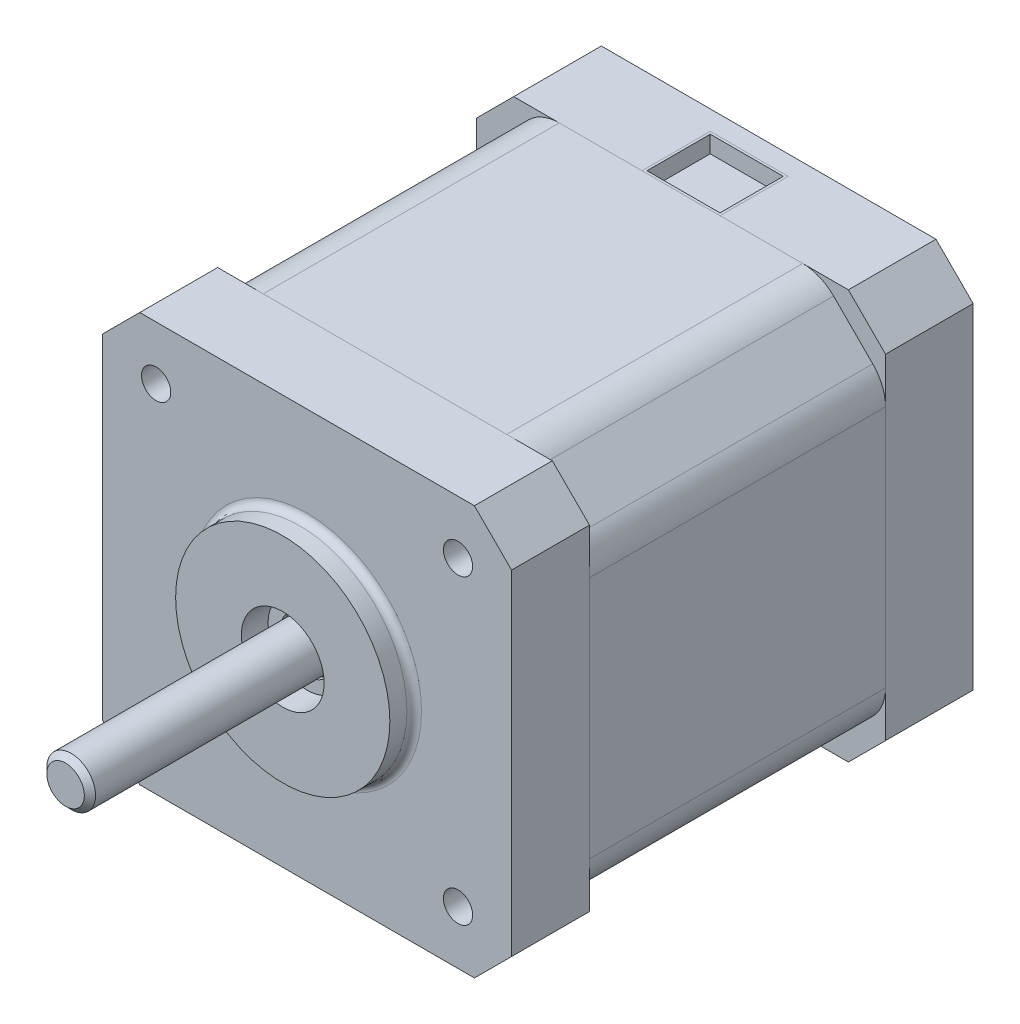
SolidWorks part; units mm, degrees
other "ŞAFT"
other "ARKA"
other "ORTA"
other "ÖN"
other "KABLO"
ref_plane "Front Plane" through (0, 0, 0) normal (0, 0, 1) x (1, 0, 0)
ref_plane "Top Plane" through (0, 0, 0) normal (0, 1, 0) x (1, 0, 0)
ref_plane "Right Plane" through (0, 0, 0) normal (1, 0, 0) x (0, 0, -1)
sketch "Sketch1" plane through (0, 0, 0) normal (0, 0, 1) x (1, 0, 0)
  line L0 (-15.5, 15.5) -> (15.5, 15.5) construction
  line L1 (17.1838, 21) -> (-17.1838, 21)
  line L2 (21, 17.1838) -> (21, -17.1838)
  line L3 (17.1838, -21) -> (-17.1838, -21)
  line L4 (-21, 17.1838) -> (-21, -17.1838)
  line L5 (19.0919, 19.0919) -> (-19.0919, -19.0919) construction
  line L6 (19.0919, -19.0919) -> (-19.0919, 19.0919) construction
  line L7 (15.5, 15.5) -> (15.5, -15.5) construction
  line L8 (15.5, -15.5) -> (-15.5, -15.5) construction
  line L9 (-15.5, -15.5) -> (-15.5, 15.5) construction
  line L10 (17.1838, 21) -> (21, 17.1838)
  line L11 (21, 17.1838) -> (21, 21) construction
  line L12 (21, 21) -> (17.1838, 21) construction
  line L13 (19.0919, 19.0919) -> (21, 21) construction
  line L14 (19.0919, 19.0919) -> (-19.0919, 19.0919) construction
  line L15 (-19.0919, 19.0919) -> (-19.0919, -19.0919) construction
  line L16 (-19.0919, -19.0919) -> (19.0919, -19.0919) construction
  line L17 (19.0919, -19.0919) -> (19.0919, 19.0919) construction
  line L18 (21, -17.1838) -> (17.1838, -21)
  line L19 (-17.1838, -21) -> (-21, -17.1838)
  line L20 (-21, 17.1838) -> (-17.1838, 21)
  line L21 (-19.0919, -19.0919) -> (-21, -21) construction
  line L22 (19.0919, -19.0919) -> (21, -21) construction
  line L23 (-19.0919, 19.0919) -> (-21, 21) construction
  line L24 (21, -17.1838) -> (21, -21) construction
  line L25 (21, -21) -> (17.1838, -21) construction
  line L26 (-17.1838, -21) -> (-21, -21) construction
  line L27 (-21, -21) -> (-21, -17.1838) construction
  line L28 (-21, 17.1838) -> (-21, 21) construction
  line L29 (-21, 21) -> (-17.1838, 21) construction
  circle A0 centre (-15.5, 15.5) radius 1.5 construction
  circle A1 centre (15.5, 15.5) radius 1.5 construction
  circle A2 centre (-15.5, -15.5) radius 1.5 construction
  circle A3 centre (15.5, -15.5) radius 1.5 construction
  point P0 (0, 0)
  dimension "D2" = 3
  dimension "D1" = 42
  dimension "D3" = 31
  dimension "D4" = 54
extrude "Boss-Extrude1" add sketch "Sketch1" against normal blind 8
sketch "Sketch3" plane through (0, 0, -8) normal (0, 0, -1) x (-1, 0, 0)
  line L0 (-19.6881, 15.6673) -> (-15.6673, 19.6881)
  line L1 (15.6673, 19.6881) -> (19.6881, 15.6673)
  line L2 (19.6881, -15.6673) -> (15.6673, -19.6881)
  line L3 (-15.6673, -19.6881) -> (-19.6881, -15.6673)
  line L4 (0, 0) -> (-17.6777, -17.6777) construction
  line L5 (0, 0) -> (17.6777, 17.6777) construction
  line L6 (-17.6777, 17.6777) -> (0, 0) construction
  line L7 (0, 0) -> (17.6777, -17.6777) construction
  line L8 (-17.1838, 21) -> (-21, 17.1838)
  line L9 (-21, 17.1838) -> (-21, -17.1838)
  line L10 (-21, -17.1838) -> (-17.1838, -21)
  line L11 (-17.1838, -21) -> (17.1838, -21)
  line L12 (17.1838, -21) -> (21, -17.1838)
  line L13 (21, -17.1838) -> (21, 17.1838)
  line L14 (21, 17.1838) -> (17.1838, 21)
  line L15 (17.1838, 21) -> (-17.1838, 21)
  line L16 (-17.6777, -17.6777) -> (-19.0919, -19.0919) construction
  line L17 (-21, 12.5) -> (-21, -12.5)
  line L18 (-17.1838, -21) -> (-21, -17.1838) construction
  line L19 (-12.5, -21) -> (12.5, -21)
  line L21 (21, -12.5) -> (21, 12.5)
  line L23 (12.5, 21) -> (-12.5, 21)
  arc A0 (-19.6881, -15.6673) -> (-21, -12.5) centre (-16.5208, -12.5) cw
  arc A1 (-15.6673, -19.6881) -> (-12.5, -21) centre (-12.5, -16.5208) ccw
  arc A2 (15.6673, -19.6881) -> (12.5, -21) centre (12.5, -16.5208) cw
  arc A3 (19.6881, -15.6673) -> (21, -12.5) centre (16.5208, -12.5) ccw
  arc A4 (19.6881, 15.6673) -> (21, 12.5) centre (16.5208, 12.5) cw
  arc A5 (15.6673, 19.6881) -> (12.5, 21) centre (12.5, 16.5208) ccw
  arc A6 (-15.6673, 19.6881) -> (-12.5, 21) centre (-12.5, 16.5208) cw
  arc A7 (-19.6881, 15.6673) -> (-21, 12.5) centre (-16.5208, 12.5) ccw
  dimension "D3" = 25
  dimension "D2" = 50
  dimension "D1" = 0
extrude "Boss-Extrude2" add sketch "Sketch3" along normal blind 30.4 separate body
sketch "Sketch4" plane through (0, 0, -38.4) normal (0, 0, -1) x (-1, 0, 0)
  line L8 (-17.1838, 21) -> (-21, 17.1838)
  line L9 (-21, 17.1838) -> (-21, -17.1838)
  line L10 (-21, -17.1838) -> (-17.1838, -21)
  line L11 (-17.1838, -21) -> (17.1838, -21)
  line L12 (17.1838, -21) -> (21, -17.1838)
  line L13 (21, -17.1838) -> (21, 17.1838)
  line L14 (21, 17.1838) -> (17.1838, 21)
  line L15 (17.1838, 21) -> (-17.1838, 21)
  line L16 (-17.1838, 21) -> (-21, 17.1838)
  line L17 (-21, 17.1838) -> (-21, -17.1838)
  line L18 (-21, -17.1838) -> (-17.1838, -21)
  line L19 (-17.1838, -21) -> (17.1838, -21)
  line L20 (17.1838, -21) -> (21, -17.1838)
  line L21 (21, -17.1838) -> (21, 17.1838)
  line L22 (21, 17.1838) -> (17.1838, 21)
  line L23 (17.1838, 21) -> (-17.1838, 21)
  dimension "D1" = 0
extrude "Boss-Extrude3" add sketch "Sketch4" along normal blind 9 separate body
sketch "Sketch5" plane through (0, 0, 0) normal (0, 0, 1) x (1, 0, 0)
  circle A0 centre (-15.5, 15.5) radius 1.5 construction
  circle A1 centre (15.5, 15.5) radius 1.5 construction
  circle A2 centre (15.5, -15.5) radius 1.5 construction
  circle A3 centre (-15.5, -15.5) radius 1.5 construction
  circle A4 centre (-15.5, 15.5) radius 1.5
  circle A5 centre (15.5, 15.5) radius 1.5
  circle A6 centre (15.5, -15.5) radius 1.5
  circle A7 centre (-15.5, -15.5) radius 1.5
extrude "Cut-Extrude1" cut sketch "Sketch5" against normal blind 4.5
sketch "Sketch6" plane through (0, 0, 0) normal (0, 0, 1) x (1, 0, 0)
  circle A0 centre (0, 0) radius 11
  dimension "D1" = 22
extrude "Boss-Extrude4" add sketch "Sketch6" along normal blind 2.5
sketch "Sketch9" plane through (0, 0, 2.5) normal (0, 0, 1) x (1, 0, 0)
  circle A0 centre (0, 0) radius 4.25
  dimension "D1" = 8.5
extrude "Cut-Extrude2" cut sketch "Sketch9" against normal blind 3
sketch "Sketch8" plane through (0, 0, -0.5) normal (0, 0, 1) x (1, 0, 0)
  circle A0 centre (0, 0) radius 2.5
  dimension "D1" = 5
extrude "Boss-Extrude5" add sketch "Sketch8" along normal blind 25.3 separate body
sketch "Sketch11" plane through (0, 0, -0.5) normal (0, 0, 1) x (1, 0, 0)
  circle A2 centre (0, 0) radius 4
  circle A3 centre (0, 0) radius 4.25 construction
  circle A4 centre (0, 0) radius 4.25 construction
  circle A5 centre (0, 0) radius 2.75
  dimension "D2" = 5.5
  dimension "D1" = 0.25
extrude "Boss-Extrude6" add sketch "Sketch11" along normal blind 0.5
fillet "Fillet1" radius 0.75 1 edges at (-11, 0, 0)
sketch "Sketch12" plane through (0, 0, 0) normal (1, 0, 0) x (0, 0, -1)
  line L0 (-24.8, 1.925) -> (-24.225, 2.5)
  line L1 (-24.8, 2.5) -> (-24.8, -2.5) construction
  line L2 (0.5, 2.5) -> (-24.8, 2.5) construction
  line L3 (-24.225, 2.5) -> (-24.225, 1.925) construction
  line L4 (-24.225, 1.925) -> (-24.8, 1.925) construction
  line L5 (-24.8, 1.925) -> (-24.8, 2.5)
  line L6 (-24.8, 2.5) -> (-24.225, 2.5)
  line L7 (-24.8, 0) -> (0, 0) construction
  dimension "D1" = 3.85
revolve "Cut-Revolve1" cut sketch "Sketch12" angle 360 about L7
sketch "Sketch13" plane through (0, 21, 0) normal (0, 1, 0) x (1, 0, 0)
  line L0 (0, 45.4) -> (0, 38.4) construction
  line L2 (-12.5, 38.4) -> (12.5, 38.4) construction
  line L3 (0, 45.4) -> (0, 47.4) construction
  line L4 (-4, 38.4) -> (4, 38.4)
  line L5 (-4, 38.4) -> (-4, 45.4)
  line L6 (-4, 45.4) -> (4, 45.4)
  line L7 (4, 38.4) -> (4, 45.4)
  line L8 (-17.1838, 47.4) -> (17.1838, 47.4) construction
  dimension "D1" = 2
  dimension "D2" = 8
extrude "Cut-Extrude3" cut sketch "Sketch13" against normal blind 2
sketch "Sketch14" plane through (0, 19, 0) normal (0, 1, 0) x (1, 0, 0)
  line L4 (-4, 45.4) -> (-4, 38.4)
  line L5 (-4, 38.4) -> (4, 38.4)
  line L6 (4, 38.4) -> (4, 45.4)
  line L7 (4, 45.4) -> (-4, 45.4)
  line L8 (-4, 45.4) -> (-4, 38.4)
  line L9 (-4, 38.4) -> (4, 38.4)
  line L10 (4, 38.4) -> (4, 45.4)
  line L11 (4, 45.4) -> (-4, 45.4)
  dimension "D1" = 0
extrude "Boss-Extrude7" add sketch "Sketch14" along normal blind 0.25 separate body
sketch "Sketch15" plane through (0, 19.25, 0) normal (0, 1, 0) x (1, 0, 0)
  line L0 (3.75, 38.65) -> (3.75, 45.15)
  line L1 (3.75, 45.15) -> (-3.75, 45.15)
  line L2 (-3.75, 45.15) -> (-3.75, 38.65)
  line L3 (-3.75, 38.65) -> (3.75, 38.65)
  line L4 (4, 45.4) -> (-4, 45.4)
  line L5 (-4, 45.4) -> (-4, 38.4)
  line L6 (-4, 38.4) -> (4, 38.4)
  line L7 (4, 38.4) -> (4, 45.4)
  line L8 (4, 45.4) -> (-4, 45.4)
  line L9 (-4, 45.4) -> (-4, 38.4)
  line L10 (-4, 38.4) -> (4, 38.4)
  line L11 (4, 38.4) -> (4, 45.4)
  dimension "D1" = 0
  dimension "D2" = 0.25
extrude "Boss-Extrude8" add sketch "Sketch15" along normal up to surface (1.75 mm away) up to face at (0, 21, -42.4)
